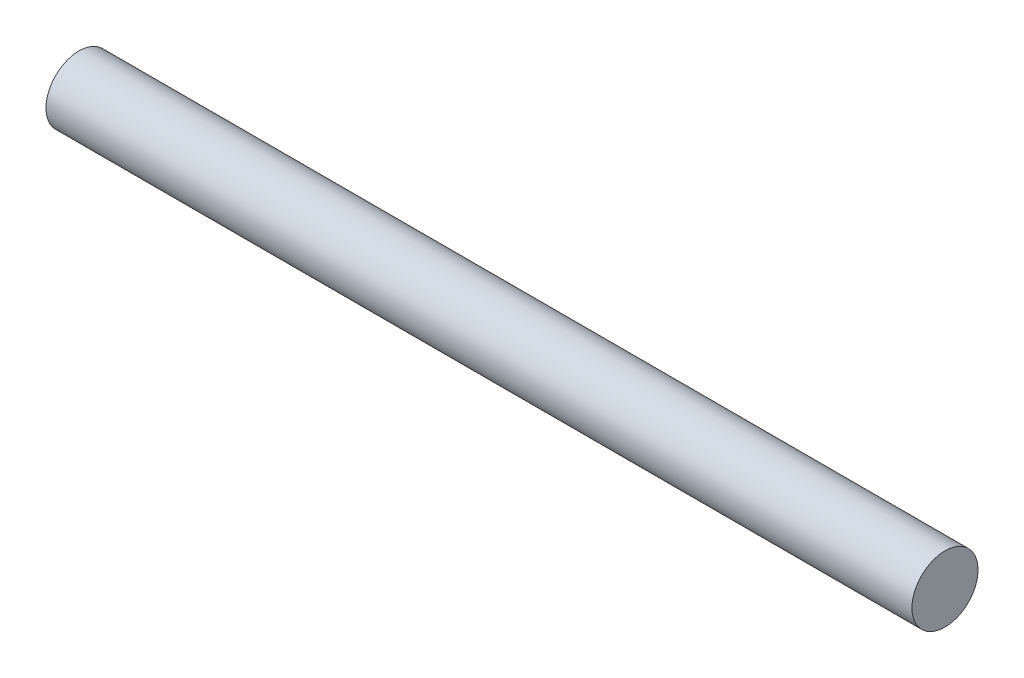
SolidWorks part; units mm, degrees
ref_plane "Front Plane" through (0, 0, 0) normal (0, 0, 1) x (1, 0, 0)
ref_plane "Top Plane" through (0, 0, 0) normal (0, 1, 0) x (1, 0, 0)
ref_plane "Right Plane" through (0, 0, 0) normal (1, 0, 0) x (0, 0, -1)
sketch "Sketch2" plane through (0, 0, 0) normal (1, 0, 0) x (0, 0, -1)
  circle A0 centre (0, 0) radius 1.985
  dimension "D1" = 3.97
extrude "Boss-Extrude1" add sketch "Sketch2" along normal blind 52
